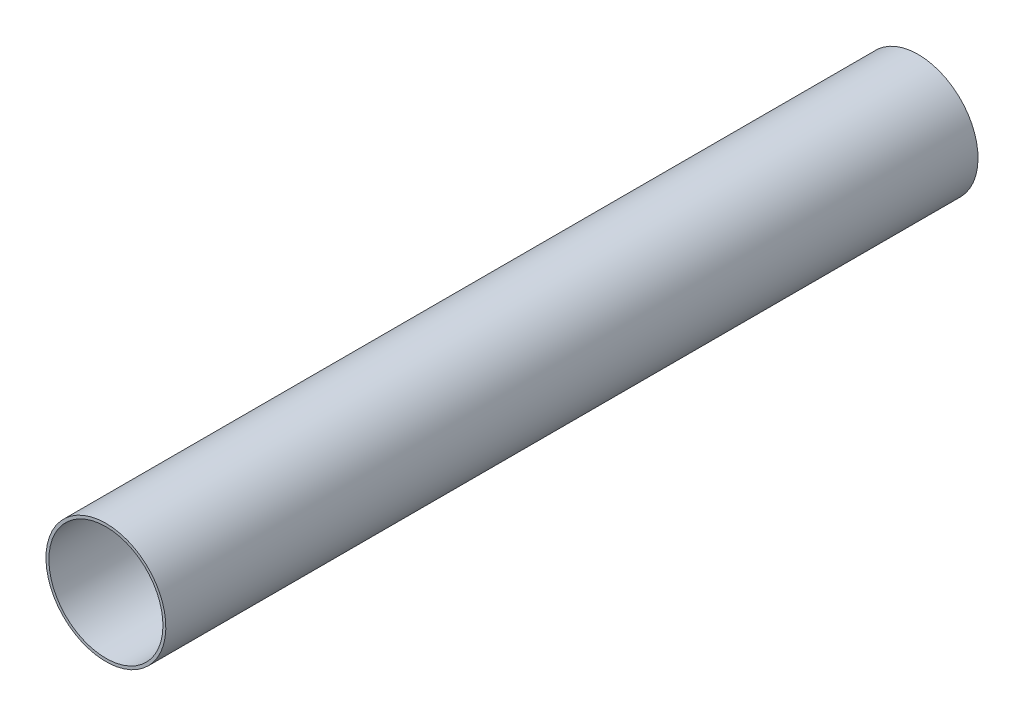
SolidWorks part; units mm, degrees
ref_plane "Plan de face" through (0, 0, 0) normal (0, 0, 1) x (1, 0, 0)
ref_plane "Plan de dessus" through (0, 0, 0) normal (0, 1, 0) x (1, 0, 0)
ref_plane "Plan de droite" through (0, 0, 0) normal (1, 0, 0) x (0, 0, -1)
sketch "Esquisse2" plane through (0, 0, 0) normal (1, 0, 0) x (0, 0, -1)
  line L0 (-10, 51.649) -> (-10, 49.149)
  line L2 (-10, 49.149) -> (-710, 49.149)
  line L12 (0, 49.149) -> (-388.9502, 49.149) construction
  line L19 (-710, 49.149) -> (-710, 51.649)
  line L20 (-710, 51.649) -> (-10, 51.649)
  line L24 (0, 0) -> (-694.9162, 0) construction
  dimension "D1" = 10
  dimension "D2" = 700
  dimension "D3" = 2.5
revolve "Révolution1" add sketch "Esquisse2" angle 360 about L24
